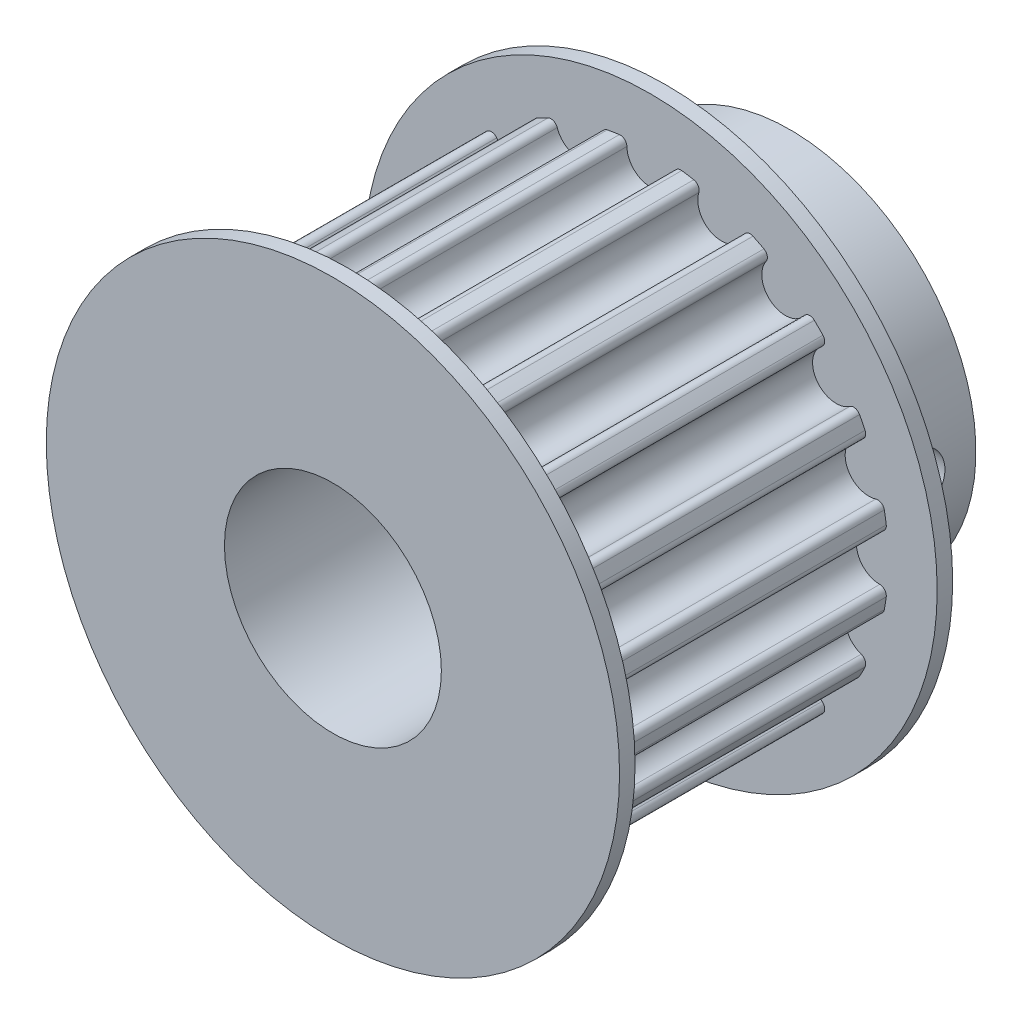
SolidWorks part; units mm, degrees
ref_plane "Front Plane" through (0, 0, 0) normal (0, 0, 1) x (1, 0, 0)
ref_plane "Top Plane" through (0, 0, 0) normal (0, 1, 0) x (1, 0, 0)
ref_plane "Right Plane" through (0, 0, 0) normal (1, 0, 0) x (0, 0, -1)
sketch "Sketch1" plane through (0, 0, 0) normal (0, 0, 1) x (1, 0, 0)
  line L0 (0, 0) -> (0, 20.3531) construction
  line L1 (13.285, 0) -> (29.1866, 0) construction
  line L2 (4.1053, 12.6348) -> (6.0513, 18.6239) construction
  arc A2 (0, 13.285) -> (1.5249, 14.7915) centre (0, 14.81) ccw
  arc A3 (2.0112, 15.2126) -> (1.5249, 14.7915) centre (1.9549, 14.7863) ccw
  arc A4 (3.1206, 14.5388) -> (4.1053, 12.6348) centre (4.5765, 14.0851) ccw
  arc A5 (3.1206, 14.5388) -> (2.7882, 15.0896) centre (2.7101, 14.6667) ccw
  arc A6 (2.7882, 15.0896) -> (2.0112, 15.2126) centre (0, 0) ccw
  arc A7 (4.1053, 12.6348) -> (6.0211, 13.5964) centre (4.5765, 14.0851) ccw
  arc A8 (6.6137, 13.8466) -> (6.0211, 13.5964) centre (6.4284, 13.4586) ccw
  arc A9 (7.3147, 13.4894) -> (6.6137, 13.8466) centre (0, 0) ccw
  arc A10 (7.4606, 12.8629) -> (7.3147, 13.4894) centre (7.1097, 13.1114) ccw
  arc A11 (7.4606, 12.8629) -> (7.8087, 10.7478) centre (8.7051, 11.9815) ccw
  arc A12 (7.8087, 10.7478) -> (9.9279, 11.0703) centre (8.7051, 11.9815) ccw
  arc A13 (10.5689, 11.1251) -> (9.9279, 11.0703) centre (10.2727, 10.8134) ccw
  arc A14 (11.1251, 10.5689) -> (10.5689, 11.1251) centre (0, 0) ccw
  arc A15 (11.0703, 9.9279) -> (11.1251, 10.5689) centre (10.8134, 10.2727) ccw
  arc A16 (11.0703, 9.9279) -> (10.7478, 7.8087) centre (11.9815, 8.7051) ccw
  arc A17 (10.7478, 7.8087) -> (12.8629, 7.4606) centre (11.9815, 8.7051) ccw
  arc A18 (13.4894, 7.3147) -> (12.8629, 7.4606) centre (13.1114, 7.1097) ccw
  arc A19 (13.8466, 6.6137) -> (13.4894, 7.3147) centre (0, 0) ccw
  arc A20 (13.5964, 6.0211) -> (13.8466, 6.6137) centre (13.4586, 6.4284) ccw
  arc A21 (13.5964, 6.0211) -> (12.6348, 4.1053) centre (14.0851, 4.5765) ccw
  arc A22 (12.6348, 4.1053) -> (14.5388, 3.1206) centre (14.0851, 4.5765) ccw
  arc A23 (15.0896, 2.7882) -> (14.5388, 3.1206) centre (14.6667, 2.7101) ccw
  arc A24 (15.2126, 2.0112) -> (15.0896, 2.7882) centre (0, 0) ccw
  arc A25 (14.7915, 1.5249) -> (15.2126, 2.0112) centre (14.7863, 1.9549) ccw
  arc A26 (14.7915, 1.5249) -> (13.285, 0) centre (14.81, 0) ccw
  arc A27 (13.285, 0) -> (14.7915, -1.5249) centre (14.81, 0) ccw
  arc A28 (15.2126, -2.0112) -> (14.7915, -1.5249) centre (14.7863, -1.9549) ccw
  arc A29 (15.0896, -2.7882) -> (15.2126, -2.0112) centre (0, 0) ccw
  arc A30 (14.5388, -3.1206) -> (15.0896, -2.7882) centre (14.6667, -2.7101) ccw
  arc A31 (14.5388, -3.1206) -> (12.6348, -4.1053) centre (14.0851, -4.5765) ccw
  arc A32 (12.6348, -4.1053) -> (13.5964, -6.0211) centre (14.0851, -4.5765) ccw
  arc A33 (13.8466, -6.6137) -> (13.5964, -6.0211) centre (13.4586, -6.4284) ccw
  arc A34 (13.4894, -7.3147) -> (13.8466, -6.6137) centre (0, 0) ccw
  arc A35 (12.8629, -7.4606) -> (13.4894, -7.3147) centre (13.1114, -7.1097) ccw
  arc A36 (12.8629, -7.4606) -> (10.7478, -7.8087) centre (11.9815, -8.7051) ccw
  arc A37 (10.7478, -7.8087) -> (11.0703, -9.9279) centre (11.9815, -8.7051) ccw
  arc A38 (11.1251, -10.5689) -> (11.0703, -9.9279) centre (10.8134, -10.2727) ccw
  arc A39 (10.5689, -11.1251) -> (11.1251, -10.5689) centre (0, 0) ccw
  arc A40 (9.9279, -11.0703) -> (10.5689, -11.1251) centre (10.2727, -10.8134) ccw
  arc A41 (9.9279, -11.0703) -> (7.8087, -10.7478) centre (8.7051, -11.9815) ccw
  arc A42 (7.8087, -10.7478) -> (7.4606, -12.8629) centre (8.7051, -11.9815) ccw
  arc A43 (7.3147, -13.4894) -> (7.4606, -12.8629) centre (7.1097, -13.1114) ccw
  arc A44 (6.6137, -13.8466) -> (7.3147, -13.4894) centre (0, 0) ccw
  arc A45 (6.0211, -13.5964) -> (6.6137, -13.8466) centre (6.4284, -13.4586) ccw
  arc A46 (6.0211, -13.5964) -> (4.1053, -12.6348) centre (4.5765, -14.0851) ccw
  arc A47 (4.1053, -12.6348) -> (3.1206, -14.5388) centre (4.5765, -14.0851) ccw
  arc A48 (2.7882, -15.0896) -> (3.1206, -14.5388) centre (2.7101, -14.6667) ccw
  arc A49 (2.0112, -15.2126) -> (2.7882, -15.0896) centre (0, 0) ccw
  arc A50 (1.5249, -14.7915) -> (2.0112, -15.2126) centre (1.9549, -14.7863) ccw
  arc A51 (1.5249, -14.7915) -> (0, -13.285) centre (0, -14.81) ccw
  arc A52 (0, -13.285) -> (-1.5249, -14.7915) centre (0, -14.81) ccw
  arc A53 (-2.0112, -15.2126) -> (-1.5249, -14.7915) centre (-1.9549, -14.7863) ccw
  arc A54 (-2.7882, -15.0896) -> (-2.0112, -15.2126) centre (0, 0) ccw
  arc A55 (-3.1206, -14.5388) -> (-2.7882, -15.0896) centre (-2.7101, -14.6667) ccw
  arc A56 (-3.1206, -14.5388) -> (-4.1053, -12.6348) centre (-4.5765, -14.0851) ccw
  arc A57 (-4.1053, -12.6348) -> (-6.0211, -13.5964) centre (-4.5765, -14.0851) ccw
  arc A58 (-6.6137, -13.8466) -> (-6.0211, -13.5964) centre (-6.4284, -13.4586) ccw
  arc A59 (-7.3147, -13.4894) -> (-6.6137, -13.8466) centre (0, 0) ccw
  arc A60 (-7.4606, -12.8629) -> (-7.3147, -13.4894) centre (-7.1097, -13.1114) ccw
  arc A61 (-7.4606, -12.8629) -> (-7.8087, -10.7478) centre (-8.7051, -11.9815) ccw
  arc A62 (-7.8087, -10.7478) -> (-9.9279, -11.0703) centre (-8.7051, -11.9815) ccw
  arc A63 (-10.5689, -11.1251) -> (-9.9279, -11.0703) centre (-10.2727, -10.8134) ccw
  arc A64 (-11.1251, -10.5689) -> (-10.5689, -11.1251) centre (0, 0) ccw
  arc A65 (-11.0703, -9.9279) -> (-11.1251, -10.5689) centre (-10.8134, -10.2727) ccw
  arc A66 (-11.0703, -9.9279) -> (-10.7478, -7.8087) centre (-11.9815, -8.7051) ccw
  arc A67 (-10.7478, -7.8087) -> (-12.8629, -7.4606) centre (-11.9815, -8.7051) ccw
  arc A68 (-13.4894, -7.3147) -> (-12.8629, -7.4606) centre (-13.1114, -7.1097) ccw
  arc A69 (-13.8466, -6.6137) -> (-13.4894, -7.3147) centre (0, 0) ccw
  arc A70 (-13.5964, -6.0211) -> (-13.8466, -6.6137) centre (-13.4586, -6.4284) ccw
  arc A71 (-13.5964, -6.0211) -> (-12.6348, -4.1053) centre (-14.0851, -4.5765) ccw
  arc A72 (-12.6348, -4.1053) -> (-14.5388, -3.1206) centre (-14.0851, -4.5765) ccw
  arc A73 (-15.0896, -2.7882) -> (-14.5388, -3.1206) centre (-14.6667, -2.7101) ccw
  arc A74 (-15.2126, -2.0112) -> (-15.0896, -2.7882) centre (0, 0) ccw
  arc A75 (-14.7915, -1.5249) -> (-15.2126, -2.0112) centre (-14.7863, -1.9549) ccw
  arc A76 (-14.7915, -1.5249) -> (-13.285, 0) centre (-14.81, 0) ccw
  arc A77 (-13.285, 0) -> (-14.7915, 1.5249) centre (-14.81, 0) ccw
  arc A78 (-15.2126, 2.0112) -> (-14.7915, 1.5249) centre (-14.7863, 1.9549) ccw
  arc A79 (-15.0896, 2.7882) -> (-15.2126, 2.0112) centre (0, 0) ccw
  arc A80 (-14.5388, 3.1206) -> (-15.0896, 2.7882) centre (-14.6667, 2.7101) ccw
  arc A81 (-14.5388, 3.1206) -> (-12.6348, 4.1053) centre (-14.0851, 4.5765) ccw
  arc A82 (-12.6348, 4.1053) -> (-13.5964, 6.0211) centre (-14.0851, 4.5765) ccw
  arc A83 (-13.8466, 6.6137) -> (-13.5964, 6.0211) centre (-13.4586, 6.4284) ccw
  arc A84 (-13.4894, 7.3147) -> (-13.8466, 6.6137) centre (0, 0) ccw
  arc A85 (-12.8629, 7.4606) -> (-13.4894, 7.3147) centre (-13.1114, 7.1097) ccw
  arc A86 (-12.8629, 7.4606) -> (-10.7478, 7.8087) centre (-11.9815, 8.7051) ccw
  arc A87 (-10.7478, 7.8087) -> (-11.0703, 9.9279) centre (-11.9815, 8.7051) ccw
  arc A88 (-11.1251, 10.5689) -> (-11.0703, 9.9279) centre (-10.8134, 10.2727) ccw
  arc A89 (-10.5689, 11.1251) -> (-11.1251, 10.5689) centre (0, 0) ccw
  arc A90 (-9.9279, 11.0703) -> (-10.5689, 11.1251) centre (-10.2727, 10.8134) ccw
  arc A91 (-9.9279, 11.0703) -> (-7.8087, 10.7478) centre (-8.7051, 11.9815) ccw
  arc A92 (-7.8087, 10.7478) -> (-7.4606, 12.8629) centre (-8.7051, 11.9815) ccw
  arc A93 (-7.3147, 13.4894) -> (-7.4606, 12.8629) centre (-7.1097, 13.1114) ccw
  arc A94 (-6.6137, 13.8466) -> (-7.3147, 13.4894) centre (0, 0) ccw
  arc A95 (-6.0211, 13.5964) -> (-6.6137, 13.8466) centre (-6.4284, 13.4586) ccw
  arc A96 (-6.0211, 13.5964) -> (-4.1053, 12.6348) centre (-4.5765, 14.0851) ccw
  arc A97 (-4.1053, 12.6348) -> (-3.1206, 14.5388) centre (-4.5765, 14.0851) ccw
  arc A98 (-2.7882, 15.0896) -> (-3.1206, 14.5388) centre (-2.7101, 14.6667) ccw
  arc A99 (-2.0112, 15.2126) -> (-2.7882, 15.0896) centre (0, 0) ccw
  arc A100 (-1.5249, 14.7915) -> (-2.0112, 15.2126) centre (-1.9549, 14.7863) ccw
  arc A101 (-1.5249, 14.7915) -> (0, 13.285) centre (0, 14.81) ccw
  point P3 (0, 0)
  point P209 (0, 0)
  dimension "D1" = 20
  dimension "D3" = 3.05
  dimension "D4" = 0.86
  dimension "D6" = 3.05
  dimension "D7" = 0.86
extrude "Boss-Extrude1" add sketch "Sketch1" along normal blind 19.5
sketch "Sketch2" plane through (0, 0, 0) normal (0, 0, -1) x (-1, 0, 0)
  circle A0 centre (0, 0) radius 18.5
  dimension "D1" = 37
extrude "Boss-Extrude2" add sketch "Sketch2" along normal blind 1
ref_plane "Plane1" through (0, 0, 9.75) normal (0, 0, 1) x (1, 0, 0)
mirror "Mirror1" about plane through (0, 0, 9.75) normal (0, 0, 1) of "Boss-Extrude2"
sketch "Sketch3" plane through (0, 0, -1) normal (0, 0, -1) x (-1, 0, 0)
  circle A0 centre (0, 0) radius 12
  dimension "D1" = 24
extrude "Boss-Extrude3" add sketch "Sketch3" along normal blind 8
sketch "Sketch4" plane through (0, 0, -9) normal (0, 0, -1) x (-1, 0, 0)
  circle A0 centre (0, 0) radius 7
  dimension "D1" = 14
extrude "Cut-Extrude1" cut sketch "Sketch4" against normal through all
sketch "Sketch5" plane through (0, 0, 0) normal (0, 1, 0) x (1, 0, 0)
  line L0 (12, 9) -> (-12, 9) construction
  circle A0 centre (0, 5) radius 2
  dimension "D1" = 4
  dimension "D2" = 4
extrude "Cut-Extrude2" cut sketch "Sketch5" against normal through all
pattern_circular "CirPattern1" count 2 every 90 about axis through (0, 0, -9) along (0, 0, 1) of "Cut-Extrude2"
